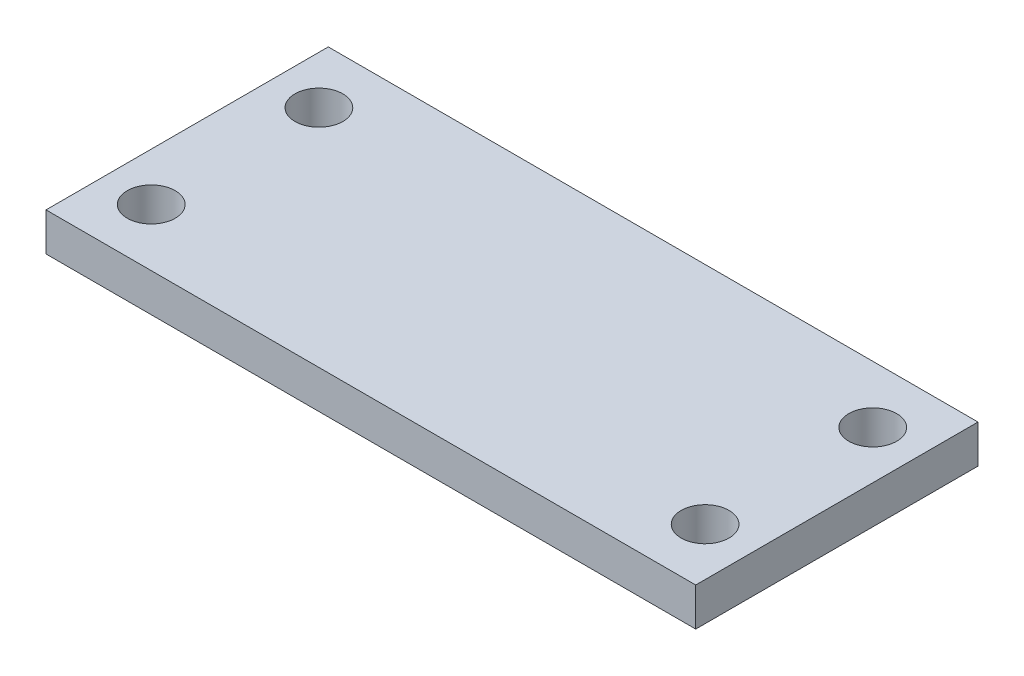
SolidWorks part; units mm, degrees
ref_plane "Front Plane" through (0, 0, 0) normal (0, 0, 1) x (1, 0, 0)
ref_plane "Top Plane" through (0, 0, 0) normal (0, 1, 0) x (1, 0, 0)
ref_plane "Right Plane" through (0, 0, 0) normal (1, 0, 0) x (0, 0, -1)
sketch "Sketch1" plane through (0, 0, 0) normal (0, 1, 0) x (1, 0, 0)
  line L0 (0, 0) -> (0, 29.464)
  line L1 (0, 29.464) -> (67.818, 29.464)
  line L2 (67.818, 29.464) -> (67.818, 0)
  line L3 (67.818, 0) -> (0, 0)
  line L4 (33.909, 29.464) -> (33.909, 0) construction
  line L5 (0, 14.732) -> (67.818, 14.732) construction
  circle A0 centre (5.0038, 23.4823) radius 2.5019
  circle A1 centre (62.8142, 23.4823) radius 2.5019
  circle A2 centre (62.8142, 5.9817) radius 2.5019
  circle A3 centre (5.0038, 5.9817) radius 2.5019
  point P7 (0, 0)
  point P10 (0, 8.1441)
  point P13 (0, 14.732)
  dimension "D4" = 5.0038
  dimension "D1" = 67.818
  dimension "D2" = 29.464
  dimension "D3" = 8.7503
  dimension "D5" = 5.0038
  dimension "D6" = 14.732
extrude "Boss-Extrude1" add sketch "Sketch1" along normal blind 3.9878
